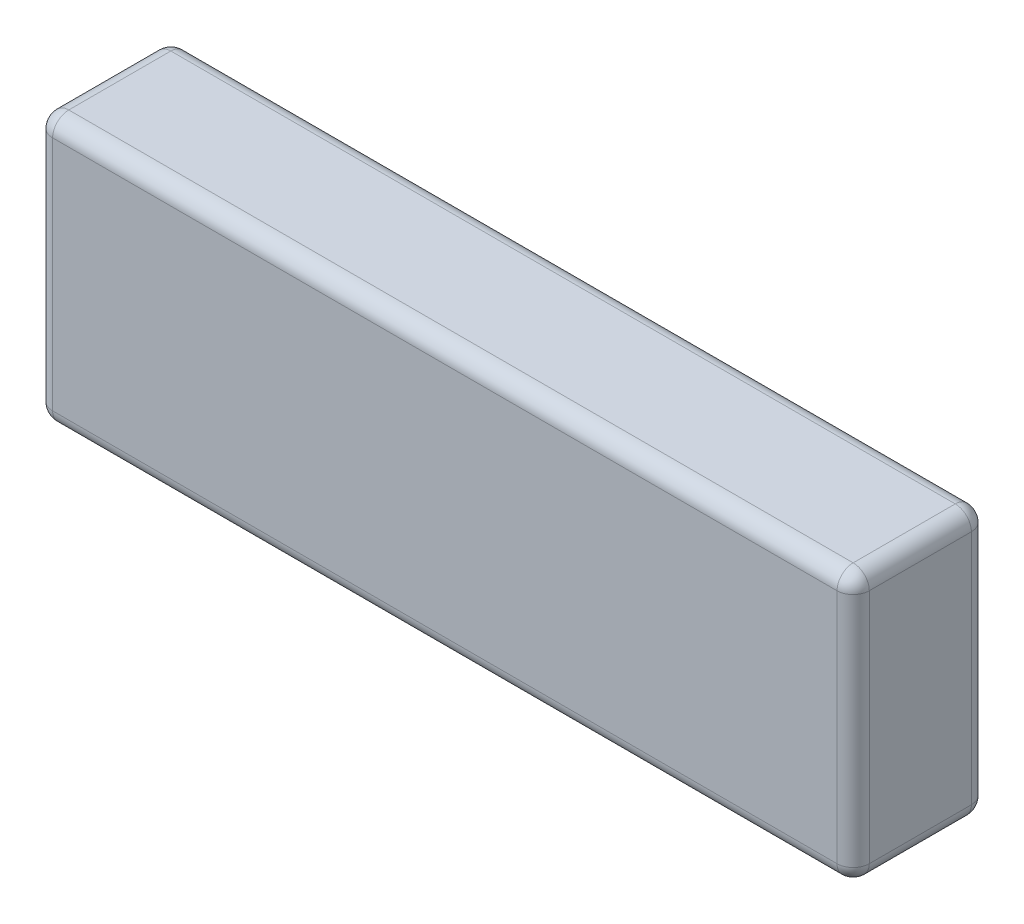
SolidWorks part; units mm, degrees
ref_plane "Front Plane" through (0, 0, 0) normal (0, 0, 1) x (1, 0, 0)
ref_plane "Top Plane" through (0, 0, 0) normal (0, 1, 0) x (1, 0, 0)
ref_plane "Right Plane" through (0, 0, 0) normal (1, 0, 0) x (0, 0, -1)
sketch "Sketch1" plane through (0, 0, 0) normal (0, 1, 0) x (1, 0, 0)
  line L1 (-76, 12.5) -> (76, 12.5)
  line L2 (-76, 12.5) -> (-76, -12.5)
  line L3 (-76, -12.5) -> (76, -12.5)
  line L4 (76, 12.5) -> (76, -12.5)
  line L5 (-76, 12.5) -> (76, -12.5) construction
  line L6 (-76, -12.5) -> (76, 12.5) construction
  point P0 (0, 0)
  dimension "D1" = 25
  dimension "D2" = 152
extrude "Boss-Extrude1" add sketch "Sketch1" along normal blind 50
fillet "Fillet1" radius 3 12 edges at (-76, 50, 0) (-76, 0, 0) (0, 50, -12.5) (-76, 25, -12.5) (0, 0, -12.5) (76, 50, 0) (76, 25, -12.5) (76, 0, 0) (-76, 25, 12.5) (0, 50, 12.5) (76, 25, 12.5) (0, 0, 12.5)
